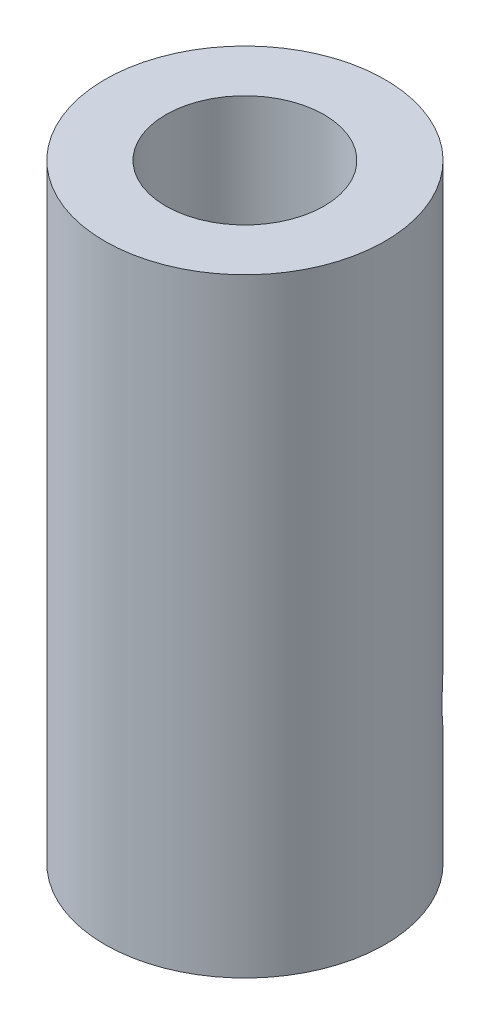
SolidWorks part; units mm, degrees
ref_plane "Front Plane" through (0, 0, 0) normal (0, 0, 1) x (1, 0, 0)
ref_plane "Top Plane" through (0, 0, 0) normal (0, 1, 0) x (1, 0, 0)
ref_plane "Right Plane" through (0, 0, 0) normal (1, 0, 0) x (0, 0, -1)
sketch "Sketch1" plane through (0, 0, 0) normal (0, 1, 0) x (1, 0, 0)
  circle A0 centre (0, 0) radius 2.6
  circle A1 centre (0, 0) radius 4.6
  dimension "D1" = 5.2
  dimension "D2" = 9.2
extrude "Boss-Extrude1" add sketch "Sketch1" along normal blind 20
sketch "Sketch2" plane through (0, 0, 0) normal (0, 0, 1) x (1, 0, 0)
  circle A0 centre (0, 5) radius 1.4
  dimension "D1" = 2.8
  dimension "D2" = 5
extrude "Cut-Extrude1" [suppressed] cut sketch "Sketch2" against normal mid plane 20
extrude "Cut-Extrude2" cut sketch "Sketch3" against normal blind 8
sketch "Sketch3" plane through (-1.472, -1.4583, -9.9015) normal (0.5449, 0, -0.8385) x (-0.8385, 0, -0.5449)
  circle A0 centre (-6.63, 6.2898) radius 1.4
